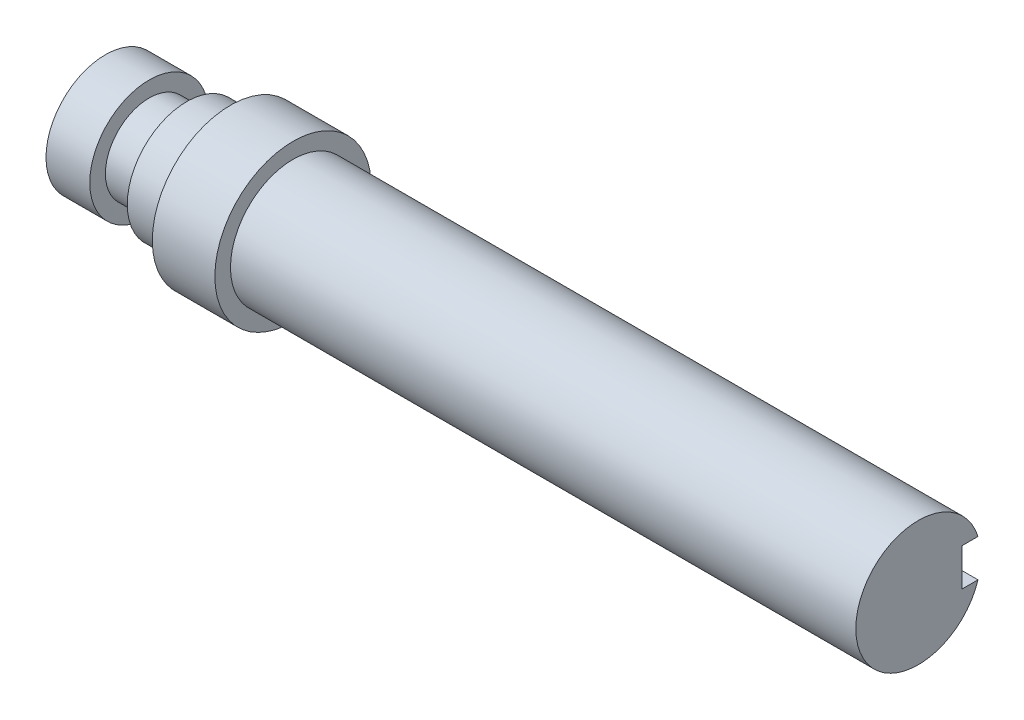
SolidWorks part; units mm, degrees
ref_plane "Front Plane" through (0, 0, 0) normal (0, 0, 1) x (1, 0, 0)
ref_plane "Top Plane" through (0, 0, 0) normal (0, 1, 0) x (1, 0, 0)
ref_plane "Right Plane" through (0, 0, 0) normal (1, 0, 0) x (0, 0, -1)
sketch "Sketch1" plane through (0, 0, 0) normal (0, 1, 0) x (1, 0, 0)
  line L0 (0, 0) -> (130, 0)
  line L1 (130, 0) -> (130, 10)
  line L2 (130, 10) -> (30, 10)
  line L3 (30, 10) -> (30, 12.5)
  line L4 (30, 12.5) -> (20, 12.5)
  line L5 (20, 12.5) -> (20, 9.5)
  line L6 (20, 9.5) -> (13, 9.5)
  line L7 (13, 9.5) -> (13, 7)
  line L8 (13, 7) -> (7, 7)
  line L9 (0, 9.5) -> (7, 9.5)
  line L10 (7, 9.5) -> (7, 7)
  line L12 (0, 9.5) -> (0, 0)
  dimension "D1" = 10
  dimension "D2" = 100
  dimension "D3" = 10
  dimension "D4" = 7
  dimension "D5" = 6
  dimension "D6" = 7
  dimension "D7" = 9.5
  dimension "D8" = 7
  dimension "D9" = 9.5
  dimension "D10" = 12.5
revolve "Revolve1" add sketch "Sketch1" angle 360 about L0
sketch "Sketch2" plane through (0, 0, 0) normal (0, 1, 0) x (1, 0, 0)
  line L0 (30, -10) -> (30, 10) construction
  line L1 (30, -10) -> (130, -10) construction
  line L2 (130, 10) -> (30, 10) construction
  line L3 (130, -10) -> (130, 10) construction
  line L4 (30, -10) -> (30, 10)
  line L5 (30, -10) -> (130, -10)
  line L6 (130, 10) -> (30, 10)
  line L7 (130, -10) -> (130, 10)
  line L8 (230, 0) -> (30, 0)
  line L9 (130, 10) -> (110, 10)
  line L10 (130, 10) -> (130, 7)
  line L11 (130, 7) -> (110, 7)
  line L12 (110, 10) -> (110, 7)
  line L13 (130, -10) -> (30, -10)
  line L16 (130, -7) -> (130, -10)
  point P11 (130, 0)
  dimension "D1" = 3
  dimension "D2" = 20
extrude "Cut-Extrude1" cut sketch "Sketch2" against normal mid plane 6 contours L11 L12 L9 L10
